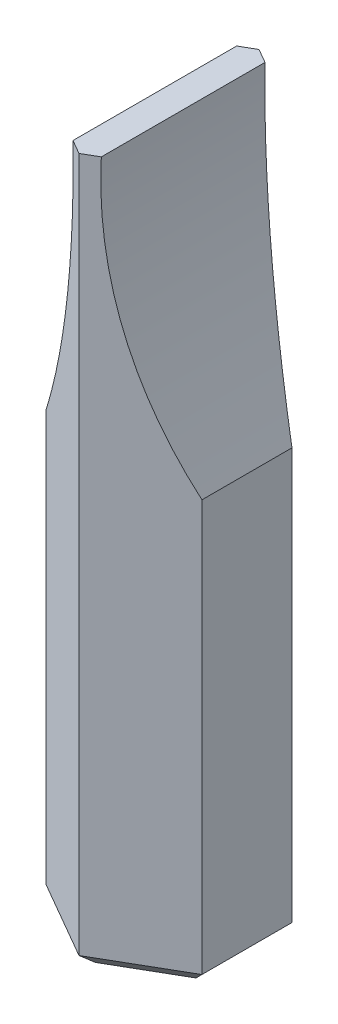
SolidWorks part; units mm, degrees
ref_plane "Front Plane" through (0, 0, 0) normal (0, 0, 1) x (1, 0, 0)
ref_plane "Top Plane" through (0, 0, 0) normal (0, 1, 0) x (1, 0, 0)
ref_plane "Right Plane" through (0, 0, 0) normal (1, 0, 0) x (0, 0, -1)
sketch "Sketch1" plane through (0, 0, 0) normal (0, 1, 0) x (1, 0, 0)
  line L1 (0, 3.175) -> (-2.7496, 1.5875)
  line L2 (-2.7496, 1.5875) -> (-2.7496, -1.5875)
  line L3 (-2.7496, -1.5875) -> (0, -3.175)
  line L4 (0, -3.175) -> (2.7496, -1.5875)
  line L5 (2.7496, -1.5875) -> (2.7496, 1.5875)
  line L6 (2.7496, 1.5875) -> (0, 3.175)
  circle A0 centre (0, 0) radius 2.7496 construction
  dimension "D1" = 6.35
extrude "Boss-Extrude1" add sketch "Sketch1" along normal blind 25
sketch "Sketch2" plane through (0, 0, 0) normal (0, 0, 1) x (1, 0, 0)
  line L1 (-2.7496, 25) -> (-0.5, 25)
  line L2 (-2.7496, 25) -> (-2.7496, 15)
  line L3 (0.5, 25) -> (2.7496, 25)
  line L4 (2.7496, 25) -> (2.7496, 15)
  line L6 (0, 25) -> (0, 0) construction
  arc A0 (-0.5, 25) -> (-2.7496, 15) centre (-20.6488, 24.2797) cw
  arc A1 (0.5, 25) -> (2.7496, 15) centre (20.6488, 24.2797) ccw
extrude "Cut-Extrude1" cut sketch "Sketch2" against normal through all both and the other way through all
chamfer "Chamfer1" distance 0.5 angle 45 6 edges at (-1.3748, 0, -2.3812) (-2.7496, 0, 0) (-1.3748, 0, 2.3813) (1.3748, 0, 2.3812) (2.7496, 0, 0) (1.3748, 0, -2.3813)
